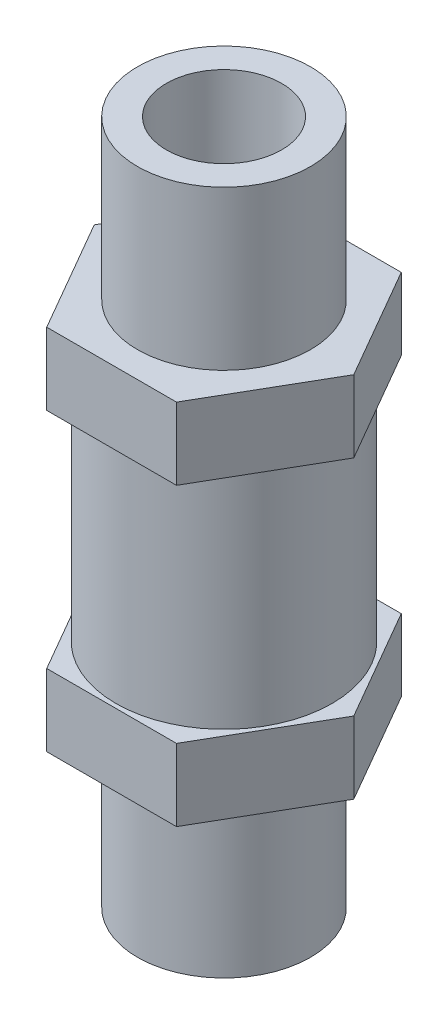
SolidWorks part; units mm, degrees
ref_plane "Спереди" through (0, 0, 0) normal (0, 0, 1) x (1, 0, 0)
ref_plane "Сверху" through (0, 0, 0) normal (0, 1, 0) x (1, 0, 0)
ref_plane "Справа" through (0, 0, 0) normal (1, 0, 0) x (0, 0, -1)
sketch "Эскиз2" plane through (0, 0, 0) normal (0, 0, 1) x (1, 0, 0)
  line L0 (0, 15.4602) -> (0, 23.9602) construction
  line L1 (4, -4.5398) -> (6, -4.5398)
  line L2 (6, -4.5398) -> (6, 6.4602)
  line L3 (6, 6.4602) -> (9, 6.4602)
  line L4 (9, 6.4602) -> (9, 11.4602)
  line L5 (7.5, 11.4602) -> (9, 11.4602)
  line L6 (7.5, 11.4602) -> (7.5, 26.9602)
  line L7 (4, 42.9602) -> (6, 42.9602)
  line L8 (6, 42.9602) -> (6, 31.9602)
  line L9 (6, 31.9602) -> (9, 31.9602)
  line L10 (9, 31.9602) -> (9, 26.9602)
  line L11 (9, 26.9602) -> (7.5, 26.9602)
  line L12 (0, 15.4602) -> (0, 23.9602)
  line L13 (4, -4.5398) -> (4, 5.4602)
  line L14 (4, 5.4602) -> (2.5, 5.4602)
  line L15 (4, 42.9602) -> (4, 32.9602)
  line L16 (4, 32.9602) -> (2.5, 32.9602)
  line L17 (0, 43.21) -> (0, 86.0204) construction
  line L18 (0, 15.4602) -> (2.5, 15.4602)
  line L19 (2.5, 15.4602) -> (2.5, 5.4602)
  line L20 (2.5, 32.9602) -> (2.5, 23.9602)
  line L21 (2.5, 23.9602) -> (0, 23.9602)
  dimension "D1" = 6
  dimension "D2" = 11
  dimension "D3" = 9
  dimension "D4" = 47.5
  dimension "D5" = 7.5
  dimension "D6" = 5
  dimension "D7" = 11
  dimension "D8" = 5
  dimension "D9" = 6
  dimension "D10" = 9
  dimension "D11" = 10
  dimension "D12" = 10
  dimension "D13" = 4
  dimension "D14" = 4
  dimension "D15" = 2.5
  dimension "D16" = 10
  dimension "D17" = 2.5
  dimension "D18" = 19
revolve "Повернуть1" add sketch "Эскиз2" angle 360 about L0
sketch "Эскиз3" plane through (0, 31.9602, 0) normal (0, 1, 0) x (1, 0, 0)
  line L1 (9, 0) -> (4.5, 7.7942)
  line L2 (4.5, 7.7942) -> (-4.5, 7.7942)
  line L3 (-4.5, 7.7942) -> (-9, 0)
  line L4 (-9, 0) -> (-4.5, -7.7942)
  line L5 (-4.5, -7.7942) -> (4.5, -7.7942)
  line L6 (4.5, -7.7942) -> (9, 0)
  circle A0 centre (0, 0) radius 7.7942 construction
  circle A1 centre (0, 0) radius 9
  circle M2 centre (0, 0) radius 9
extrude "Вырез-Вытянуть1" cut sketch "Эскиз3" against normal blind 30 contours L3 M2 | L2 M2 | L1 M2 | L6 M2 | L5 M2 | L4 M2
